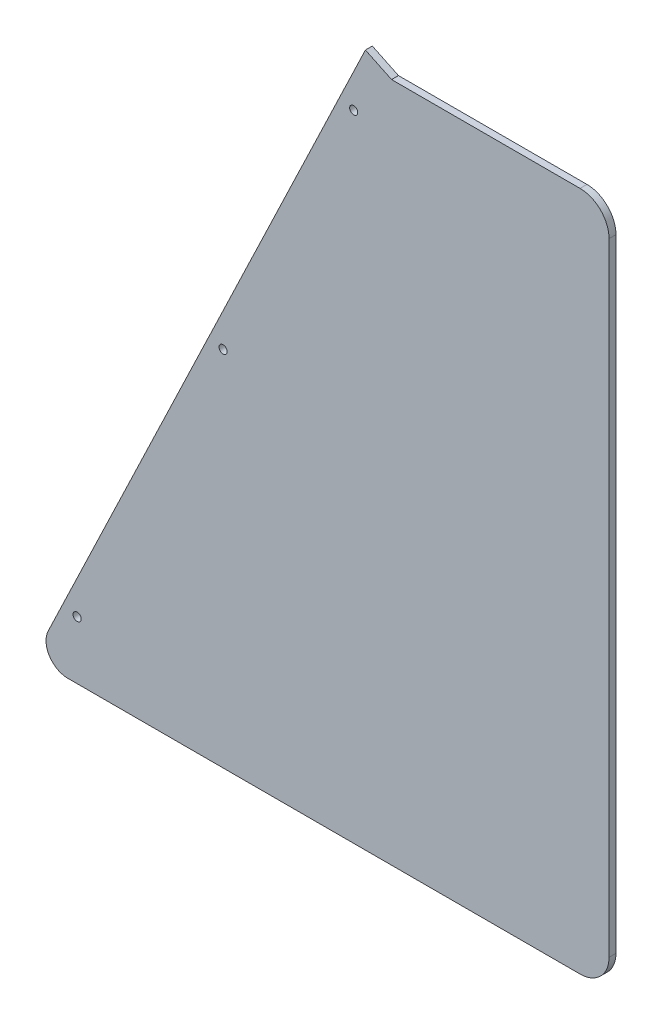
SolidWorks part; units mm, degrees
material "Acrylic (Medium-high impact)"
ref_plane "Front Plane" through (0, 0, 0) normal (0, 0, 1) x (1, 0, 0)
ref_plane "Top Plane" through (0, 0, 0) normal (0, 1, 0) x (1, 0, 0)
ref_plane "Right Plane" through (0, 0, 0) normal (1, 0, 0) x (0, 0, -1)
sketch "Sketch1" plane through (0, 0, 0) normal (0, 0, 1) x (1, 0, 0)
  line L0 (103.9447, 0) -> (-249.3625, 0)
  line L1 (-262.8887, 21.4839) -> (-44.0903, 477.9275)
  line L3 (-44.0903, 477.9275) -> (-26.0553, 469.2823)
  line L4 (123.9447, 449.2823) -> (123.9447, 20)
  line L5 (-26.0553, 469.2823) -> (103.9447, 469.2823)
  circle A1 centre (-52.175, 437.9275) radius 2.8
  circle A2 centre (-142.2589, 250) radius 2.8
  circle A3 centre (-242.9234, 40) radius 2.8
  arc A4 (-249.3625, 0) -> (-262.8887, 21.4839) centre (-249.3625, 15) cw
  arc A5 (123.9447, 20) -> (103.9447, 0) centre (103.9447, 20) cw
  arc A7 (123.9447, 449.2823) -> (103.9447, 469.2823) centre (103.9447, 449.2823) ccw
  point P6 (0, 0)
  point P15 (-273.1871, 0)
  point P21 (123.9447, 469.2823)
  dimension "D4" = 5.6
  dimension "D11" = 15
  dimension "D13" = 20
  dimension "D14" = 150
  dimension "D15" = 20
  dimension "D2" = 530
  dimension "D3" = 64.389
  dimension "D5" = 10
  dimension "D6" = 10
  dimension "D7" = 10
  dimension "D8" = 40
  dimension "D9" = 40
  dimension "D10" = 250
  dimension "D12" = 20
extrude "Boss-Extrude1" add sketch "Sketch1" against normal blind 4.7625
